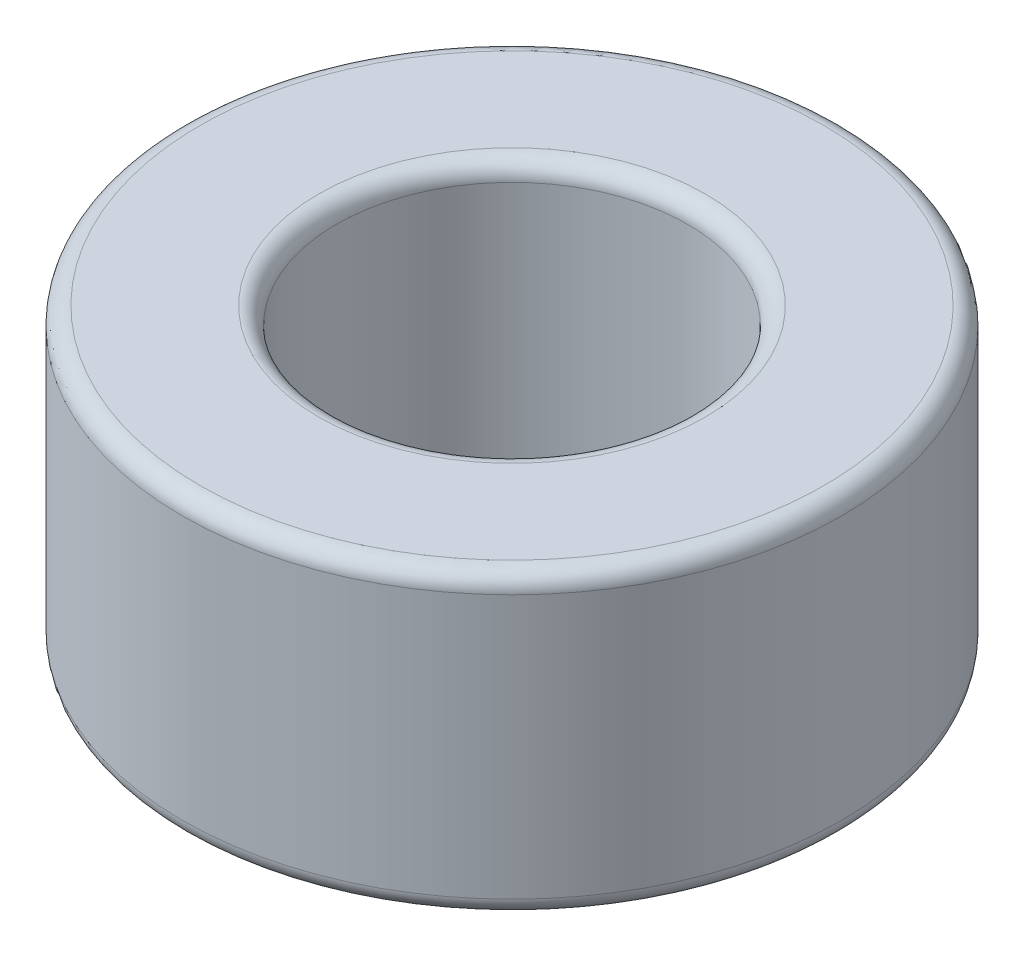
SolidWorks part; units mm, degrees
ref_plane "Front Plane" through (0, 0, 0) normal (0, 0, 1) x (1, 0, 0)
ref_plane "Top Plane" through (0, 0, 0) normal (0, 1, 0) x (1, 0, 0)
ref_plane "Right Plane" through (0, 0, 0) normal (1, 0, 0) x (0, 0, -1)
sketch "Sketch1" plane through (0, 0, 0) normal (0, 1, 0) x (1, 0, 0)
  circle A0 centre (0, 0) radius 5.08
  circle A1 centre (0, 0) radius 9.525
  dimension "D1" = 10.16
  dimension "D2" = 19.05
extrude "Boss-Extrude1" add sketch "Sketch1" along normal blind 8.636
fillet "Fillet1" radius 0.508 4 edges at (0, 8.636, 5.08) (0, 8.636, 9.525) (0, 0, 5.08) (0, 0, 9.525)
